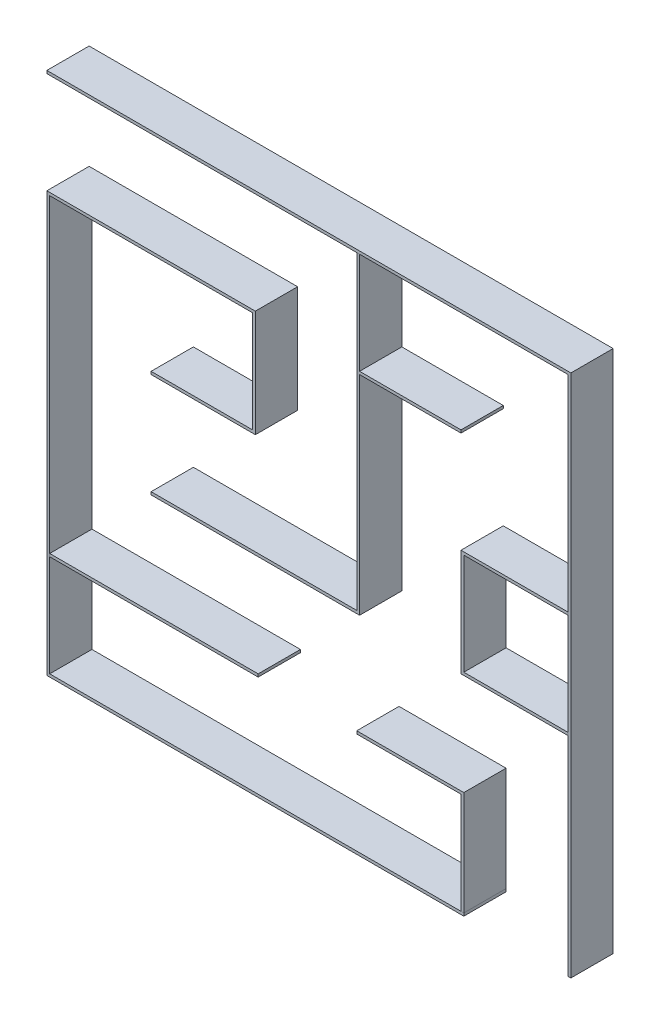
SolidWorks part; units mm, degrees
ref_plane "Front Plane" through (0, 0, 0) normal (0, 0, 1) x (1, 0, 0)
ref_plane "Top Plane" through (0, 0, 0) normal (0, 1, 0) x (1, 0, 0)
ref_plane "Right Plane" through (0, 0, 0) normal (1, 0, 0) x (0, 0, -1)
sketch "Sketch1" plane through (0, 0, 0) normal (0, 0, 1) x (1, 0, 0)
  line L1 (-930, -930) -> (930, -930)
  line L2 (-930, -930) -> (-930, 930)
  line L3 (-930, 930) -> (930, 930)
  line L4 (930, -930) -> (930, 930)
  line L5 (-930, -930) -> (930, 930) construction
  line L6 (-930, 930) -> (930, -930) construction
  point P0 (0, 0)
  dimension "D1" = 1860
  dimension "D2" = 1860
extrude "Boss-Extrude1" add sketch "Sketch1" along normal blind 10
sketch "Sketch2" plane through (0, 0, 10) normal (0, 0, 1) x (1, 0, 0)
  line L0 (930, 930) -> (930, -930)
  line L1 (930, -930) -> (-930, -930)
  line L2 (-930, -930) -> (-930, 930)
  line L3 (-930, 930) -> (930, 930)
extrude "Extrude-Thin1" add sketch "Sketch2" along normal blind 150 separate body thin
sketch "Sketch3" plane through (0, 0, 10) normal (0, 0, 1) x (1, 0, 0)
  line L0 (-930, -930) -> (930, -930) construction
  line L1 (-920, -560) -> (920, -560)
  line L2 (-920, -560) -> (-920, -550)
  line L3 (-920, -550) -> (920, -550)
  line L4 (920, -560) -> (920, -550)
  line L5 (-920, -560) -> (920, -550) construction
  line L6 (-920, -550) -> (920, -560) construction
  point P0 (0, -555)
  dimension "D1" = 10
  dimension "D2" = 1840
  dimension "D3" = 0
  dimension "D4" = 370
extrude "Boss-Extrude2" add sketch "Sketch3" along normal blind 150
pattern_linear "LPattern1" count 4 spacing 370 along (0, 1, 0) of "Boss-Extrude2"
sketch "Sketch4" plane through (0, 0, 10) normal (0, 0, 1) x (1, 0, 0)
  line L0 (920, -920) -> (920, 920) construction
  line L1 (540, 920) -> (550, 920)
  line L2 (540, 920) -> (540, -920)
  line L3 (540, -920) -> (550, -920)
  line L4 (550, 920) -> (550, -920)
  line L5 (540, 920) -> (550, -920) construction
  line L6 (540, -920) -> (550, 920) construction
  point P0 (545, 0)
  dimension "D1" = 10
  dimension "D2" = 1840
  dimension "D3" = 0
  dimension "D4" = 370
extrude "Boss-Extrude3" add sketch "Sketch4" along normal blind 150
pattern_linear "LPattern2" count 4 spacing 370 along (-1, 0, 0) of "Boss-Extrude3"
sketch "Sketch8" plane through (0, 0, 160) normal (0, 0, 1) x (1, 0, 0)
  line L0 (550, -560) -> (920, -560) construction
  line L1 (550, -550) -> (920, -550)
  line L2 (550, -550) -> (550, -560)
  line L3 (550, -560) -> (920, -560)
  line L4 (920, -550) -> (920, -560)
  line L5 (550, -560) -> (920, -560) construction
  line L7 (550, 560) -> (920, 560)
  line L8 (550, 560) -> (550, 550)
  line L9 (550, 550) -> (920, 550)
  line L10 (920, 560) -> (920, 550)
  line L11 (-190, -550) -> (170, -550)
  line L12 (-190, -550) -> (-190, -560)
  line L13 (-190, -560) -> (170, -560)
  line L14 (170, -550) -> (170, -560)
  line L15 (180, -560) -> (170, -560)
  line L16 (180, -560) -> (180, -920)
  line L17 (180, -920) -> (170, -920)
  line L18 (170, -560) -> (170, -920)
  line L19 (-200, -560) -> (-190, -560)
  line L20 (-200, -560) -> (-200, -920)
  line L21 (-200, -920) -> (-190, -920)
  line L22 (-190, -560) -> (-190, -920)
  line L23 (-570, -560) -> (-560, -560)
  line L24 (-570, -560) -> (-570, -920)
  line L25 (-570, -920) -> (-560, -920)
  line L26 (-560, -560) -> (-560, -920)
  line L27 (-570, -180) -> (-920, -180)
  line L28 (-570, -180) -> (-570, -190)
  line L29 (-570, -190) -> (-920, -190)
  line L30 (-920, -180) -> (-920, -190)
  line L31 (-570, 190) -> (-920, 190)
  line L32 (-570, 190) -> (-570, 180)
  line L33 (-570, 180) -> (-920, 180)
  line L34 (-920, 190) -> (-920, 180)
  line L35 (-570, 920) -> (-560, 920)
  line L36 (-570, 920) -> (-570, 560)
  line L37 (-570, 560) -> (-560, 560)
  line L38 (-560, 920) -> (-560, 560)
  line L39 (-200, 920) -> (-190, 920)
  line L40 (-200, 920) -> (-200, 560)
  line L41 (-200, 560) -> (-190, 560)
  line L42 (-190, 920) -> (-190, 560)
  line L43 (-570, 550) -> (-560, 550)
  line L44 (-570, 550) -> (-570, 190)
  line L45 (-570, 190) -> (-560, 190)
  line L46 (-560, 550) -> (-560, 190)
  line L47 (-570, 180) -> (-560, 180)
  line L48 (-570, 180) -> (-570, -180)
  line L49 (-570, -180) -> (-560, -180)
  line L50 (-560, 180) -> (-560, -180)
  line L51 (550, -190) -> (540, -190)
  line L52 (550, -190) -> (550, -550)
  line L53 (550, -550) -> (540, -550)
  line L54 (540, -190) -> (540, -550)
  line L55 (540, 550) -> (550, 550)
  line L56 (540, 550) -> (540, 190)
  line L57 (540, 190) -> (550, 190)
  line L58 (550, 550) -> (550, 190)
  line L59 (540, 920) -> (550, 920)
  line L60 (540, 920) -> (540, 560)
  line L61 (540, 560) -> (550, 560)
  line L62 (550, 920) -> (550, 560)
extrude "Cut-Extrude6" cut sketch "Sketch8" against normal blind 150 contours L1 L4 L3 L2
sketch "Sketch9" plane through (0, 0, 160) normal (0, 0, 1) x (1, 0, 0)
  line L1 (920, 560) -> (550, 560)
  line L2 (920, 560) -> (920, 550)
  line L3 (920, 550) -> (550, 550)
  line L4 (550, 560) -> (550, 550)
extrude "Cut-Extrude7" cut sketch "Sketch9" against normal blind 150
sketch "Sketch10" plane through (0, 0, 160) normal (0, 0, 1) x (1, 0, 0)
  line L0 (180, -180) -> (180, 180) construction
  line L1 (540, 190) -> (180, 190)
  line L2 (540, 190) -> (540, 180)
  line L3 (540, 180) -> (180, 180)
  line L4 (180, 190) -> (180, 180)
  line L5 (180, -180) -> (180, 180) construction
extrude "Cut-Extrude8" cut sketch "Sketch10" against normal blind 150
sketch "Sketch11" plane through (0, 0, 160) normal (0, 0, 1) x (1, 0, 0)
  line L1 (540, -180) -> (180, -180)
  line L2 (540, -180) -> (540, -190)
  line L3 (540, -190) -> (180, -190)
  line L4 (180, -180) -> (180, -190)
extrude "Cut-Extrude9" cut sketch "Sketch11" against normal blind 150
sketch "Sketch12" plane through (0, 0, 160) normal (0, 0, 1) x (1, 0, 0)
  line L1 (540, 920) -> (550, 920)
  line L2 (540, 920) -> (540, 190)
  line L3 (540, 190) -> (550, 190)
  line L4 (550, 920) -> (550, 190)
extrude "Cut-Extrude10" cut sketch "Sketch12" against normal blind 150
sketch "Sketch13" plane through (0, 0, 160) normal (0, 0, 1) x (1, 0, 0)
  line L1 (550, -190) -> (540, -190)
  line L2 (550, -190) -> (550, -550)
  line L3 (550, -550) -> (540, -550)
  line L4 (540, -190) -> (540, -550)
extrude "Cut-Extrude11" cut sketch "Sketch13" against normal blind 150
sketch "Sketch14" plane through (0, 0, 160) normal (0, 0, 1) x (1, 0, 0)
  line L1 (-560, -560) -> (-570, -560)
  line L2 (-560, -560) -> (-560, -920)
  line L3 (-560, -920) -> (-570, -920)
  line L4 (-570, -560) -> (-570, -920)
extrude "Cut-Extrude12" cut sketch "Sketch14" against normal blind 150
sketch "Sketch15" plane through (0, 0, 160) normal (0, 0, 1) x (1, 0, 0)
  line L1 (-200, -560) -> (-190, -560)
  line L2 (-200, -560) -> (-200, -920)
  line L3 (-200, -920) -> (-190, -920)
  line L4 (-190, -560) -> (-190, -920)
extrude "Cut-Extrude13" cut sketch "Sketch15" against normal blind 150
sketch "Sketch16" plane through (0, 0, 160) normal (0, 0, 1) x (1, 0, 0)
  line L1 (180, -560) -> (170, -560)
  line L2 (180, -560) -> (180, -920)
  line L3 (180, -920) -> (170, -920)
  line L4 (170, -560) -> (170, -920)
extrude "Cut-Extrude14" cut sketch "Sketch16" against normal blind 150
sketch "Sketch17" plane through (0, 0, 160) normal (0, 0, 1) x (1, 0, 0)
  line L0 (-920, -560) -> (540, -560) construction
  line L1 (170, -550) -> (-180, -550)
  line L2 (170, -550) -> (170, -560)
  line L3 (170, -560) -> (-180, -560)
  line L4 (-180, -550) -> (-180, -560)
extrude "Cut-Extrude15" cut sketch "Sketch17" against normal blind 150
sketch "Sketch18" plane through (0, 0, 160) normal (0, 0, 1) x (1, 0, 0)
  line L1 (-190, -190) -> (-200, -190)
  line L2 (-190, -190) -> (-190, -550)
  line L3 (-190, -550) -> (-200, -550)
  line L4 (-200, -190) -> (-200, -550)
extrude "Cut-Extrude16" cut sketch "Sketch18" against normal blind 150
sketch "Sketch19" plane through (0, 0, 160) normal (0, 0, 1) x (1, 0, 0)
  line L1 (-560, -190) -> (-570, -190)
  line L2 (-560, -190) -> (-560, -550)
  line L3 (-560, -550) -> (-570, -550)
  line L4 (-570, -190) -> (-570, -550)
extrude "Cut-Extrude17" cut sketch "Sketch19" against normal blind 150
sketch "Sketch20" plane through (0, 0, 160) normal (0, 0, 1) x (1, 0, 0)
  line L1 (-560, 550) -> (-570, 550)
  line L2 (-560, 550) -> (-560, -180)
  line L3 (-560, -180) -> (-570, -180)
  line L4 (-570, 550) -> (-570, -180)
extrude "Cut-Extrude18" cut sketch "Sketch20" against normal blind 150
sketch "Sketch21" plane through (0, 0, 160) normal (0, 0, 1) x (1, 0, 0)
  line L1 (-570, 190) -> (-920, 190)
  line L2 (-570, 190) -> (-570, 180)
  line L3 (-570, 180) -> (-920, 180)
  line L4 (-920, 190) -> (-920, 180)
extrude "Cut-Extrude19" cut sketch "Sketch21" against normal blind 150
sketch "Sketch22" plane through (0, 0, 160) normal (0, 0, 1) x (1, 0, 0)
  line L1 (-190, 180) -> (-200, 180)
  line L2 (-190, 180) -> (-190, -180)
  line L3 (-190, -180) -> (-200, -180)
  line L4 (-200, 180) -> (-200, -180)
extrude "Cut-Extrude20" cut sketch "Sketch22" against normal blind 150
sketch "Sketch23" plane through (0, 0, 160) normal (0, 0, 1) x (1, 0, 0)
  line L0 (-560, 180) -> (170, 180) construction
  line L1 (170, 190) -> (-180, 190)
  line L2 (170, 190) -> (170, 180)
  line L3 (170, 180) -> (-180, 180)
  line L4 (-180, 190) -> (-180, 180)
extrude "Cut-Extrude21" cut sketch "Sketch23" against normal blind 150
sketch "Sketch24" plane through (0, 0, 160) normal (0, 0, 1) x (1, 0, 0)
  line L0 (-920, -190) -> (170, -190) construction
  line L1 (-920, -180) -> (-559.964, -180)
  line L2 (-920, -180) -> (-920, -190)
  line L3 (-920, -190) -> (-559.964, -190)
  line L4 (-559.964, -180) -> (-559.964, -190)
  dimension "D1" = 0
extrude "Cut-Extrude22" cut sketch "Sketch24" against normal blind 150
sketch "Sketch25" plane through (0, 0, 160) normal (0, 0, 1) x (1, 0, 0)
  line L1 (-570, 920) -> (-560, 920)
  line L2 (-570, 920) -> (-570, 560)
  line L3 (-570, 560) -> (-560, 560)
  line L4 (-560, 920) -> (-560, 560)
extrude "Cut-Extrude23" cut sketch "Sketch25" against normal blind 150
sketch "Sketch26" plane through (0, 0, 160) normal (0, 0, 1) x (1, 0, 0)
  line L1 (-190, 920) -> (-200, 920)
  line L2 (-190, 920) -> (-190, 560)
  line L3 (-190, 560) -> (-200, 560)
  line L4 (-200, 920) -> (-200, 560)
extrude "Cut-Extrude24" cut sketch "Sketch26" against normal blind 150
sketch "Sketch27" plane through (0, 0, 160) normal (0, 0, 1) x (1, 0, 0)
  line L1 (170, 560) -> (-190, 560)
  line L2 (170, 560) -> (170, 550)
  line L3 (170, 550) -> (-190, 550)
  line L4 (-190, 560) -> (-190, 550)
extrude "Cut-Extrude25" cut sketch "Sketch27" against normal blind 150
sketch "Sketch28" plane through (0, 0, 160) normal (0, 0, 1) x (1, 0, 0)
  line L0 (-930, -930) -> (930, -930) construction
  line L1 (920, -920) -> (550, -920)
  line L2 (920, -920) -> (920, -930)
  line L3 (920, -930) -> (550, -930)
  line L4 (550, -920) -> (550, -930)
  dimension "D1" = 370
extrude "Cut-Extrude26" cut sketch "Sketch28" against normal blind 150
sketch "Sketch30" plane through (0, 0, 160) normal (0, 0, 1) x (1, 0, 0)
  line L0 (-930, 930) -> (-930, -930) construction
  line L1 (-920, 920) -> (-930, 920)
  line L2 (-920, 920) -> (-920, 550)
  line L3 (-920, 550) -> (-930, 550)
  line L4 (-930, 920) -> (-930, 550)
  dimension "D1" = 370
extrude "Cut-Extrude29" cut sketch "Sketch30" against normal blind 150
sketch "Sketch31" plane through (0, 0, 160) normal (0, 0, 1) x (1, 0, 0)
  line L1 (170, -190) -> (180, -190)
  line L2 (170, -190) -> (170, -550)
  line L3 (170, -550) -> (180, -550)
  line L4 (180, -190) -> (180, -550)
extrude "Cut-Extrude30" cut sketch "Sketch31" against normal blind 150
sketch "Sketch32" plane through (0, 0, 10) normal (0, 0, 1) x (1, 0, 0)
  line L0 (930, -930) -> (930, 930) construction
  line L1 (930, 930) -> (-930, 930)
  line L2 (930, 930) -> (930, -930)
  line L3 (930, -930) -> (-930, -930)
  line L4 (-930, 930) -> (-930, -930)
  line L5 (-930, -930) -> (930, -930) construction
  dimension "D1" = 1860
  dimension "D2" = 1860
  dimension "D3" = 0
  dimension "D4" = 0
extrude "Cut-Extrude33" cut sketch "Sketch32" against normal blind 10
sketch "Sketch33" plane through (0, 0, 10) normal (0, 0, -1) x (-1, 0, 0)
  line L1 (190, 190) -> (180, 190)
  line L2 (190, 190) -> (190, 180)
  line L3 (190, 180) -> (180, 180)
  line L4 (180, 190) -> (180, 180)
extrude "Cut-Extrude34" cut sketch "Sketch33" against normal through all
sketch "Sketch34" plane through (-920, 0, 0) normal (-1, 0, 0) x (0, 0, 1)
  line L1 (10, 560) -> (160, 560)
  line L2 (10, 560) -> (10, 550)
  line L3 (10, 550) -> (160, 550)
  line L4 (160, 560) -> (160, 550)
extrude "Boss-Extrude4" add sketch "Sketch34" along normal blind 10
